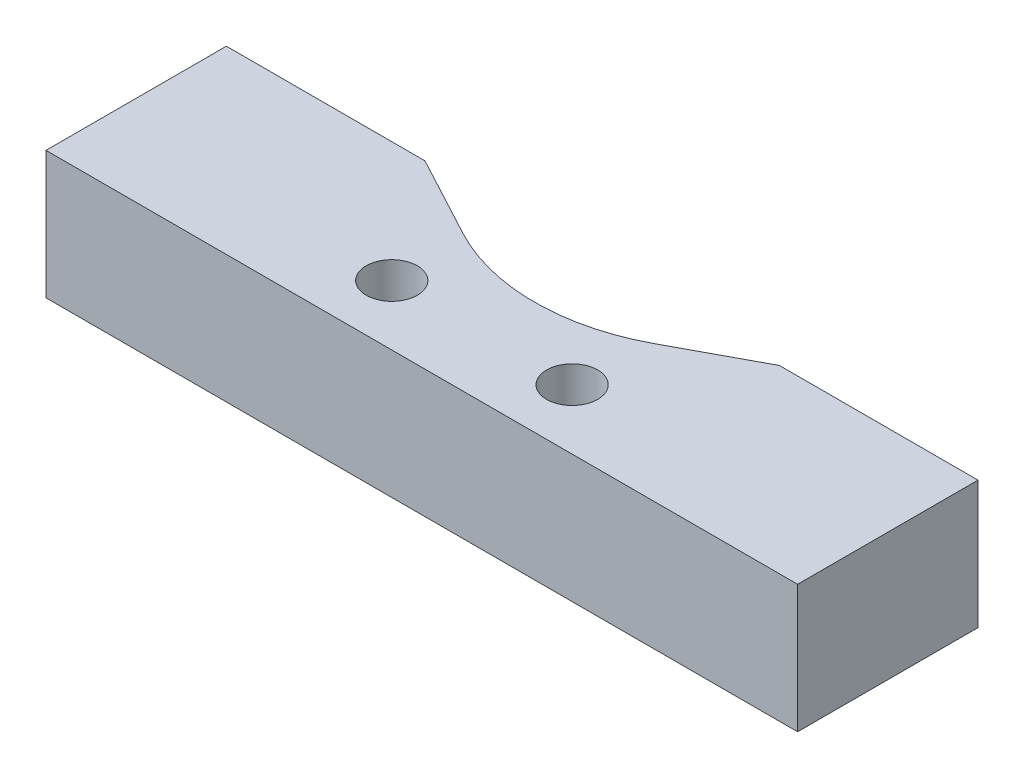
SolidWorks part; units mm, degrees
material "AISI 304"
ref_plane "前视基准面" through (0, 0, 0) normal (0, 0, 1) x (1, 0, 0)
ref_plane "上视基准面" through (0, 0, 0) normal (0, 1, 0) x (1, 0, 0)
ref_plane "右视基准面" through (0, 0, 0) normal (1, 0, 0) x (0, 0, -1)
sketch "草图1" plane through (0, 0, 0) normal (0, 1, 0) x (1, 0, 0)
  line L0 (-11.7344, 0) -> (21.6403, 0) construction
  line L1 (0, 17.054) -> (0, -18.4858) construction
  line L2 (20.3611, -4.4074) -> (6.375, -11.9) construction
  line L3 (-20.3611, -4.4074) -> (-6.375, -11.9) construction
  line L7 (20.3611, 4.4074) -> (6.375, 11.9) construction
  line L10 (-20.3611, 4.4074) -> (-6.375, 11.9) construction
  line L11 (-25, -21) -> (25, -21)
  line L12 (25, -21) -> (25, -9)
  line L13 (25, -9) -> (11.7883, -9)
  line L14 (-25, -21) -> (-25, -9)
  line L15 (-25, -9) -> (-11.7883, -9)
  line L16 (-11.7883, -9) -> (-6.375, -11.9)
  line L17 (6.375, -11.9) -> (11.7883, -9)
  circle A0 centre (0, 0) radius 4 construction
  circle A2 centre (18, 0) radius 2.5 construction
  arc A5 (20.3611, -4.4074) -> (20.3611, 4.4074) centre (18, 0) ccw construction
  arc A8 (6.375, 11.9) -> (-6.375, 11.9) centre (0, 0) ccw construction
  circle A9 centre (-18, 0) radius 2.5 construction
  arc A10 (6.375, -11.9) -> (-6.375, -11.9) centre (0, 0) cw
  arc A11 (-20.3611, -4.4074) -> (-20.3611, 4.4074) centre (-18, 0) cw construction
  point P16 (0, -21)
  dimension "D1" = 8
  dimension "D2" = 36
  dimension "D3" = 5
  dimension "D4" = 13.5
  dimension "D5" = 5
  dimension "D6" = 12
  dimension "D7" = 21
  dimension "D8" = 50
extrude "凸台-拉伸1" add sketch "草图1" along normal blind 8.5
sketch "草图2" plane through (0, 8.5, 0) normal (0, 1, 0) x (1, 0, 0)
  line L0 (0, 0) -> (0, -50000) construction
  line L1 (-25, -21) -> (25, -21) construction
  circle A0 centre (6, -17) radius 1.7
  circle A1 centre (-6, -17) radius 1.7
  dimension "D1" = 3.4
  dimension "D2" = 12
  dimension "D3" = 4
extrude "切除-拉伸1" cut sketch "草图2" against normal through all
equation "\"3。2\"=3.6998"
